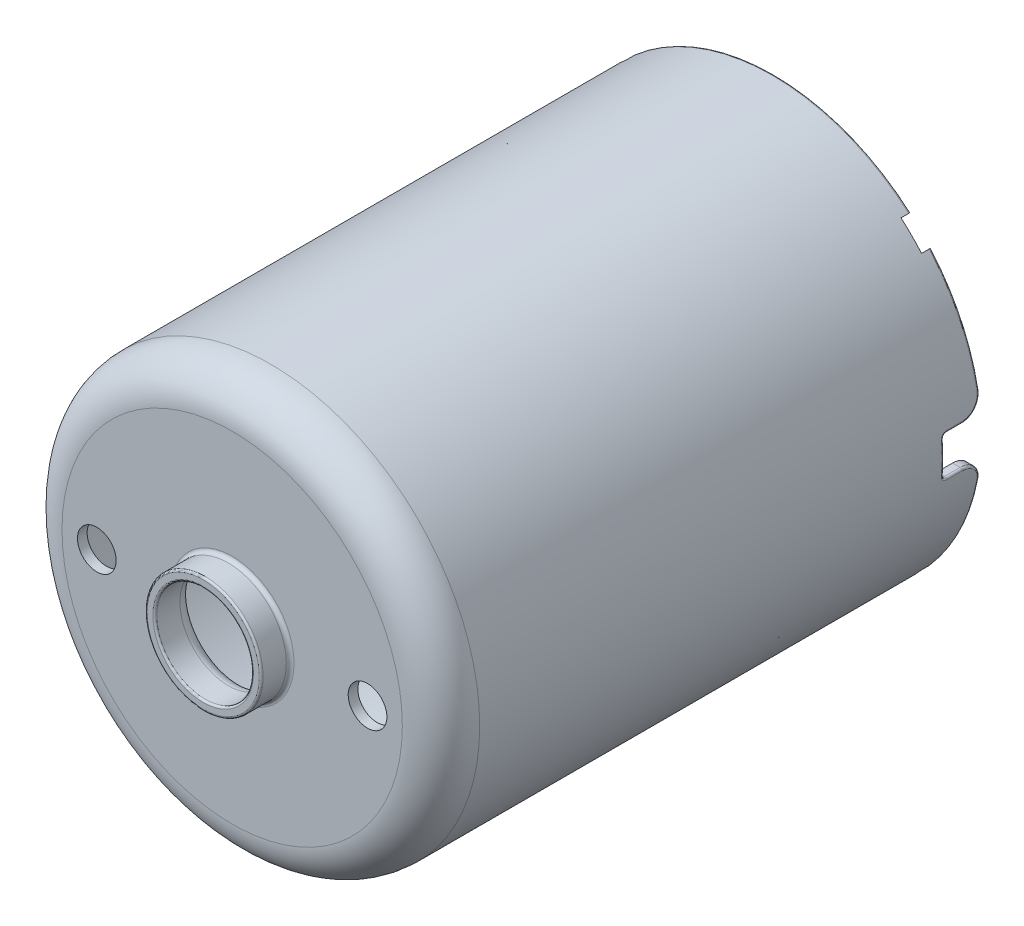
SolidWorks part; units mm, degrees
material "Chrome Stainless Steel"
ref_plane "Front Plane" through (0, 0, 0) normal (0, 0, 1) x (1, 0, 0)
ref_plane "Top Plane" through (0, 0, 0) normal (0, 1, 0) x (1, 0, 0)
ref_plane "Right Plane" through (0, 0, 0) normal (1, 0, 0) x (0, 0, -1)
sketch "Sketch1" plane through (0, 0, 0) normal (1, 0, 0) x (0, 0, -1)
  line L0 (0, 3.2) -> (0, 8.8)
  line L1 (2, 10.8) -> (28, 10.8)
  line L2 (-1.5, 3) -> (-0.2, 3)
  line L3 (0, 0) -> (-1.5, 0) construction
  line L5 (0, 3) -> (-1.5, 3) construction
  line L6 (-1.5, 0) -> (-1.5, 3) construction
  line L7 (-1.5, 2.5) -> (-0.2, 2.5)
  line L8 (0.5, 3.2) -> (0.5, 8.8)
  line L9 (2, 10.3) -> (28, 10.3)
  line L10 (28, 10.8) -> (28, 10.3)
  line L11 (-1.5, 3) -> (-1.5, 2.5)
  line L12 (0, 0) -> (28, 0) construction
  arc A0 (0, 8.8) -> (2, 10.8) centre (2, 8.8) cw
  arc A1 (0, 3.2) -> (-0.2, 3) centre (-0.2, 3.2) cw
  arc A2 (0.5, 3.2) -> (-0.2, 2.5) centre (-0.2, 3.2) cw
  arc A3 (0.5, 8.8) -> (2, 10.3) centre (2, 8.8) cw
  point P7 (-0.75, 0)
  point P10 (0, 10.8)
  dimension "D5" = 2
  dimension "D6" = 0.2
  dimension "D1" = 10.8
  dimension "D2" = 28
  dimension "D3" = 3
  dimension "D4" = 1.5
  dimension "D7" = 0.5
revolve "Revolve1" add sketch "Sketch1" angle 360 about L12
fillet "Fillet1" radius 0.1 2 edges at (2.5, 0, 1.5) (3, 0, 1.5)
sketch "Sketch2" plane through (0, 0, -28) normal (0, 0, -1) x (-1, 0, 0)
  line L0 (0, 0) -> (7.6368, 7.6368) construction
  line L1 (0.5303, -0.5303) -> (8.1671, 7.1064) construction
  line L2 (-0.5303, 0.5303) -> (7.1064, 8.1671) construction
  line L3 (7.088, 8.1486) -> (6.7335, 7.7942)
  line L4 (7.7942, 6.7335) -> (8.1486, 7.088)
  line L5 (6.7335, -7.7942) -> (7.088, -8.1486)
  line L6 (8.1486, -7.088) -> (7.7942, -6.7335)
  line L7 (-7.7942, -6.7335) -> (-8.1486, -7.088)
  line L8 (-7.088, -8.1486) -> (-6.7335, -7.7942)
  line L9 (-6.7335, 7.7942) -> (-7.088, 8.1486)
  line L10 (-8.1486, 7.088) -> (-7.7942, 6.7335)
  arc A0 (7.7942, 6.7335) -> (6.7335, 7.7942) centre (0, 0) ccw
  arc A1 (8.1486, 7.088) -> (7.088, 8.1486) centre (0, 0) ccw
  arc A2 (7.088, -8.1486) -> (8.1486, -7.088) centre (0, 0) ccw
  arc A3 (6.7335, -7.7942) -> (7.7942, -6.7335) centre (0, 0) ccw
  arc A4 (-8.1486, -7.088) -> (-7.088, -8.1486) centre (0, 0) ccw
  arc A5 (-7.7942, -6.7335) -> (-6.7335, -7.7942) centre (0, 0) ccw
  arc A6 (-7.088, 8.1486) -> (-8.1486, 7.088) centre (0, 0) ccw
  arc A7 (-6.7335, 7.7942) -> (-7.7942, 6.7335) centre (0, 0) ccw
  point P26 (0, 0)
  dimension "D1" = 0.75
  dimension "D2" = 0.75
  dimension "D3" = 4
extrude "Cut-Extrude1" cut sketch "Sketch2" against normal blind 0.5
sketch "Sketch4" plane through (0, 0, -28) normal (0, 0, -1) x (-1, 0, 0)
  line L0 (0, 0) -> (-10.8, 0) construction
  dimension "D1" = 10.8
ref_plane "Plane1" through (10.8, 0, 0) normal (1, 0, 0) x (0, 0, -1)
sketch "Sketch5" plane through (10.8, 0, 0) normal (1, 0, 0) x (0, 0, -1)
  line L0 (28, 0) -> (26, 0) construction
  line L2 (28, 2) -> (28, -2)
  line L3 (26.2, -1) -> (27, -1)
  line L4 (26, -0.8) -> (26, 0.8)
  line L5 (26.2, 1) -> (27, 1)
  line L6 (28, -1) -> (28, 1)
  line L7 (26, -1) -> (28, 1) construction
  line L8 (26, 1) -> (28, -1) construction
  arc A0 (28, 2) -> (27, 1) centre (27, 2) cw
  arc A1 (28, -2) -> (27, -1) centre (27, -2) ccw
  arc A2 (26, -0.8) -> (26.2, -1) centre (26.2, -0.8) ccw
  arc A3 (26, 0.8) -> (26.2, 1) centre (26.2, 0.8) cw
  point P5 (27, 0)
  point P12 (28, 0)
  dimension "D4" = 0.2
  dimension "D1" = 2
  dimension "D2" = 2
  dimension "D3" = 4
extrude "Cut-Extrude2" cut sketch "Sketch5" against normal up to next contours A3 L4 A2 L3 A1 L2 A0 L5
fillet "Fillet2" radius 0.1 12 edges at (9.7198, -4.7081, -28) (10.7125, -1.372, -27.7782) (10.7536, -1, -26.6) (10.7603, -0.9252, -26.0441) (10.8, 0, -26) (10.7603, 0.9252, -26.0441) (10.7536, 1, -26.6) (10.7125, 1.372, -27.7782) (0, -10.8, -28) (-10.8, 0, -28) (0, 10.8, -28) (9.7198, 4.7081, -28)
sketch "Sketch6" plane through (0, 0, 0) normal (0, 0, 1) x (1, 0, 0)
  line L0 (0, 0) -> (0, 7) construction
  circle A0 centre (0, 0) radius 7 construction
  circle A1 centre (7, 0) radius 1
  circle A2 centre (-7, 0) radius 1
  dimension "D1" = 14
  dimension "D2" = 2
extrude "Cut-Extrude3" cut sketch "Sketch6" against normal up to next
